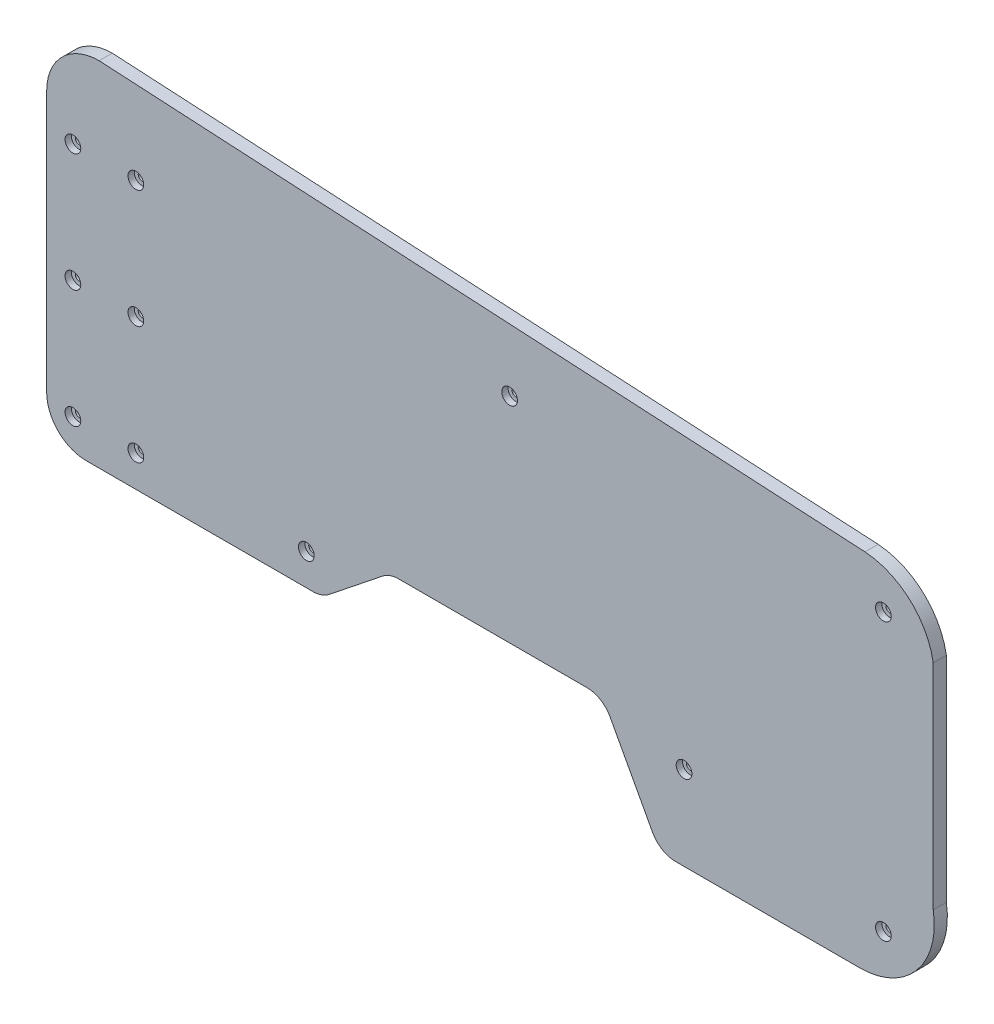
SolidWorks part; units mm, degrees
other "Folder spoin"
material "ABS PC"
ref_plane "Płaszczyzna przednia" through (0, 0, 0) normal (0, 0, 1) x (1, 0, 0)
ref_plane "Płaszczyzna górna" through (0, 0, 0) normal (0, 1, 0) x (1, 0, 0)
ref_plane "Płaszczyzna prawa" through (0, 0, 0) normal (1, 0, 0) x (0, 0, -1)
sketch "outer-wire" plane through (0, 0, 0) normal (0, 0, 1) x (1, 0, 0)
  line L0 (-24, -24.5302) -> (62.5, -24.5302)
  line L3 (-39, -9.5302) -> (-39, 90)
  line L4 (95.2361, -4) -> (167, -4)
  line L6 (176, -9.6411) -> (192, -39.2805)
  line L7 (68.7361, -22.3476) -> (89, -6.1826)
  line L10 (271, -44.5302) -> (200.7997, -44.5302)
  line L12 (299, -11.3778) -> (299, 70.2365)
  line L14 (-19, 110) -> (273, 93.8273)
  arc A0 (-39, -9.5302) -> (-24, -24.5302) centre (-24, -9.5302) ccw
  arc A1 (-19, 110) -> (-39, 90) centre (-19, 90) ccw
  arc A2 (62.5, -24.5302) -> (68.7361, -22.3476) centre (62.5, -14.5302) ccw
  arc A3 (89, -6.1826) -> (95.2361, -4) centre (95.2361, -14) cw
  arc A4 (271, -44.5302) -> (299, -11.3778) centre (271, -16.1298) ccw
  arc A5 (299, 70.2365) -> (273, 93.8273) centre (271, 65.5) ccw
  arc A6 (200.7997, -44.5302) -> (192, -39.2805) centre (200.7997, -34.5302) cw
  arc A7 (176, -9.6411) -> (167, -4) centre (167, -14) ccw
  point P14 (66, -24.5302)
  dimension "D2" = 20
  dimension "D1" = 15
  dimension "D7" = 66
  dimension "D8" = 89
  dimension "D10" = 167
  dimension "D17" = 271
  dimension "D18" = 273
  dimension "D20" = 39
  dimension "D21" = 110
  dimension "D4" = 28.4004
  dimension "D6" = 62.5
  dimension "D9" = 167
  dimension "D12" = 192
  dimension "D11" = 176
  dimension "D3" = 10
  dimension "D5" = 28.3978
  dimension "D13" = 65.5
  dimension "D14" = 4
  dimension "D15" = 71.7639
  dimension "D16" = 271
  dimension "D19" = 299
extrude "Dodanie-wyciągnięcie1" add sketch "outer-wire" along normal blind 5 contours L0 A2 L7 A3 L4 A7 L6 A6 L10 A4 L12 A5 L14 A1 L3 A0
ref_plane "Płaszczyzna6" through (0, -24.5302, 0) normal (0, -1, 0) x (-1, 0, 0)
sketch "Szkic1" plane through (0, -24.5302, 0) normal (0, -1, 0) x (-1, 0, 0)
  line L0 (24, 0) -> (-62.5, 0) construction
  line L1 (24, -5) -> (24, 0) construction
  circle A0 centre (19, 0) radius 3.5
  dimension "D1" = 7
  dimension "D2" = 5
extrude "Wytnij-wyciągnięcie1" cut sketch "Szkic1" against normal blind 100
ref_plane "Płaszczyzna12" through (0, 0, 5) normal (0, 0, 1) x (1, 0, 0)
sketch "Szkic3" plane through (0, 0, 5) normal (0, 0, 1) x (1, 0, 0)
  circle A0 centre (280, -28) radius 1.5
  circle A1 centre (280, 77.5) radius 1.5
  circle A2 centre (-5, 77.5) radius 1.5
  circle A3 centre (-29, 77.5) radius 1.5
  circle A4 centre (-29, -12.5) radius 1.5
  circle A5 centre (-29, 32.5) radius 1.5
  circle A6 centre (-5, 32.5) radius 1.5
  circle A7 centre (-5, -12.5) radius 1.5
  circle A8 centre (60, -12.5) radius 1.5
  circle A9 centre (204, -12.5) radius 1.5
  circle A10 centre (137.5, 77.5) radius 1.5
  dimension "D1" = 3
  dimension "D6" = 45
  dimension "D2" = 12.5
  dimension "D3" = 24
  dimension "D4" = 45
  dimension "D5" = 45
  dimension "D7" = 5
  dimension "D8" = 60
  dimension "D10" = 204
  dimension "D11" = 280
  dimension "D12" = 28
  dimension "D13" = 142.5
extrude "Wytnij-wyciągnięcie3" cut sketch "Szkic3" along direction (0, 0, 1) on the side against the normal blind 5 contours A4 | A5 | A3 | A2 | A6 | A7 | A8 | A10 | A9 | A0 | A1
ref_plane "Płaszczyzna13" through (0, 0, 5) normal (0, 0, 1) x (1, 0, 0)
sketch "Szkic5" plane through (0, 0, 5) normal (0, 0, 1) x (1, 0, 0)
  circle A0 centre (-29, -12.5) radius 3
  circle A1 centre (-29, 32.5) radius 3
  circle A2 centre (-29, 77.5) radius 3
  circle A3 centre (-5, 77.5) radius 3
  circle A4 centre (-5, 32.5) radius 3
  circle A5 centre (-5, -12.5) radius 3
  circle A6 centre (60, -12.5) radius 3
  circle A7 centre (137.5, 77.5) radius 3
  circle A8 centre (204, -12.5) radius 3
  circle A9 centre (280, -28) radius 3
  circle A10 centre (280, 77.5) radius 3
  dimension "D1" = 6
  dimension "D2" = 24
  dimension "D3" = 45
  dimension "D4" = 45
  dimension "D5" = 65
  dimension "D6" = 142.5
  dimension "D7" = 105.5
  dimension "D8" = 144
  dimension "D9" = 76
  dimension "D10" = 15.5
extrude "Wytnij-wyciągnięcie4" cut sketch "Szkic5" against normal blind 2.4 contours A0
mirror "Lustro4" about plane through (0, 0, 5) normal (0, 0, 1) of bodies 110
delete or keep bodies "Obiekt-Usuń/zachowaj 2" type delete bodies bodies 110
mirror "Lustro5" about plane through (-24, -9.5302, 10) normal (0, 0, -1) of bodies 111
delete or keep bodies "Obiekt-Usuń/zachowaj 4" type delete bodies bodies 111
mirror "Lustro6" about plane through (-24, -9.5302, 10) normal (0, 0, 1) of bodies 112
delete or keep bodies "Obiekt-Usuń/zachowaj 5" type delete bodies bodies 112
mirror "Lustro7" about plane through (-24, -9.5302, 10) normal (0, 0, -1) of bodies 113
delete or keep bodies "Obiekt-Usuń/zachowaj 6" type delete bodies bodies 113
